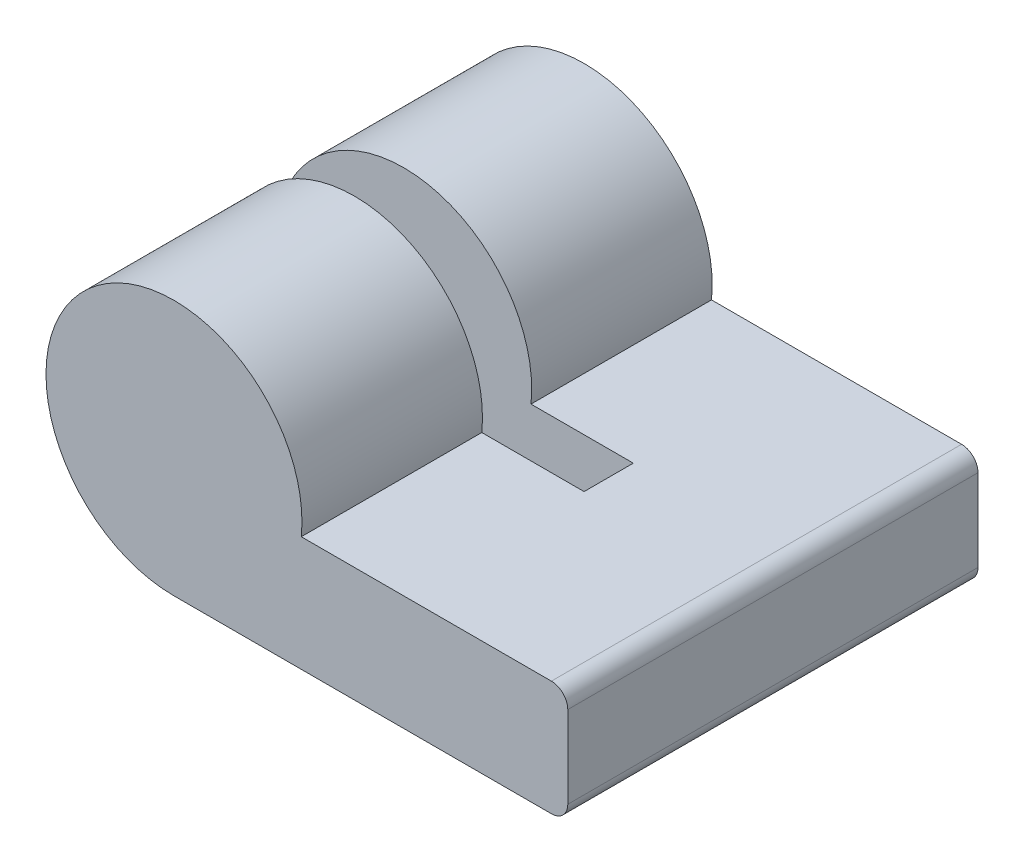
SolidWorks part; units mm, degrees
ref_plane "Plan1" through (0, 0, 0) normal (0, 0, 1) x (1, 0, 0)
ref_plane "Plan2" through (0, 0, 0) normal (0, 1, 0) x (1, 0, 0)
ref_plane "Plan3" through (0, 0, 0) normal (1, 0, 0) x (0, 0, -1)
sketch "Esquisse1" plane through (0, 0, 0) normal (0, 0, 1) x (1, 0, 0)
  line L0 (0, -3.9) -> (12, -3.9)
  line L1 (12, -3.9) -> (12, -0.4)
  line L2 (12, -0.4) -> (3.8794, -0.4)
  arc A0 (3.8794, -0.4) -> (0, -3.9) centre (0, 0) ccw
  dimension "D1" = 7.8
  dimension "D2" = 12
  dimension "D3" = 3.5
extrude "Base-Extrusion" add sketch "Esquisse1" along normal blind 12.5
fillet "Congé1" radius 0.5
ref_plane "Plan4" through (0, 0, 7) normal (0, 0, 1) x (1, 0, 0)
sketch "Esquisse2" plane through (0, 0, 7) normal (0, 0, 1) x (1, 0, 0)
  circle A0 centre (-15, 20) radius 30
  dimension "D1" = 60
  dimension "D2" = 20
  dimension "D3" = 15
extrude "Enlèv. mat.-Extru.1" cut sketch "Esquisse2" against normal blind 1.5
